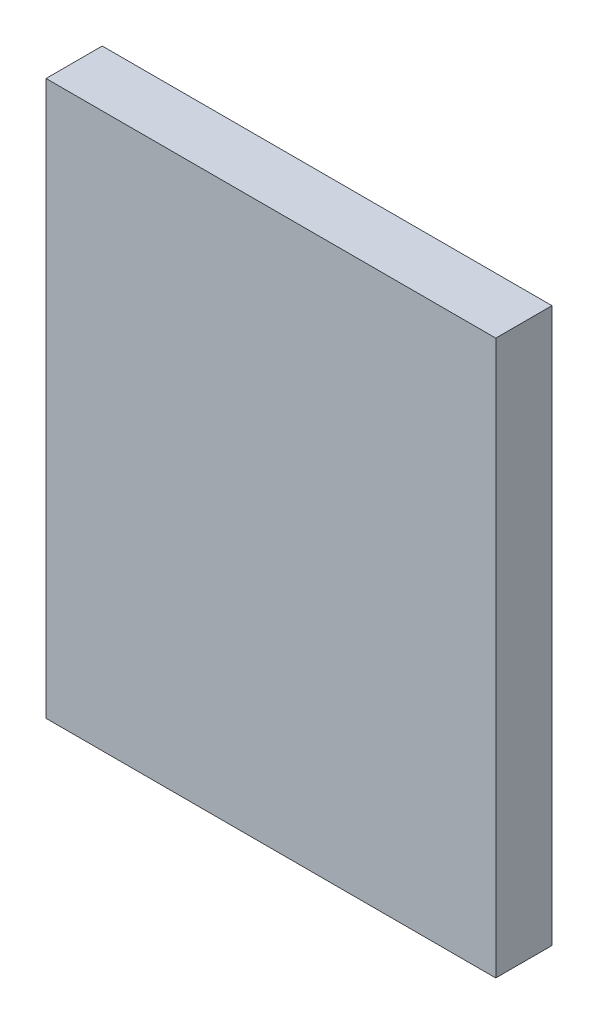
SolidWorks part; units mm, degrees
ref_plane "Front Plane" through (0, 0, 0) normal (0, 0, 1) x (1, 0, 0)
ref_plane "Top Plane" through (0, 0, 0) normal (0, 1, 0) x (1, 0, 0)
ref_plane "Right Plane" through (0, 0, 0) normal (1, 0, 0) x (0, 0, -1)
sketch "Sketch2" plane through (0, 0, 0) normal (0, 0, 1) x (1, 0, 0)
  line L0 (7.9375, -54.8106) -> (7.9375, -23.041) construction
  line L1 (3.175, -23.5124) -> (7.9375, -23.5124) construction
  line L3 (7.9375, -23.5124) -> (-17.4625, -23.5124)
  line L4 (7.9375, -23.5124) -> (7.9375, -54.8106)
  line L5 (7.9375, -54.8106) -> (-17.4625, -54.8106)
  line L6 (-17.4625, -23.5124) -> (-17.4625, -54.8106)
extrude "Boss-Extrude1" add sketch "Sketch2" along normal blind 3.175
